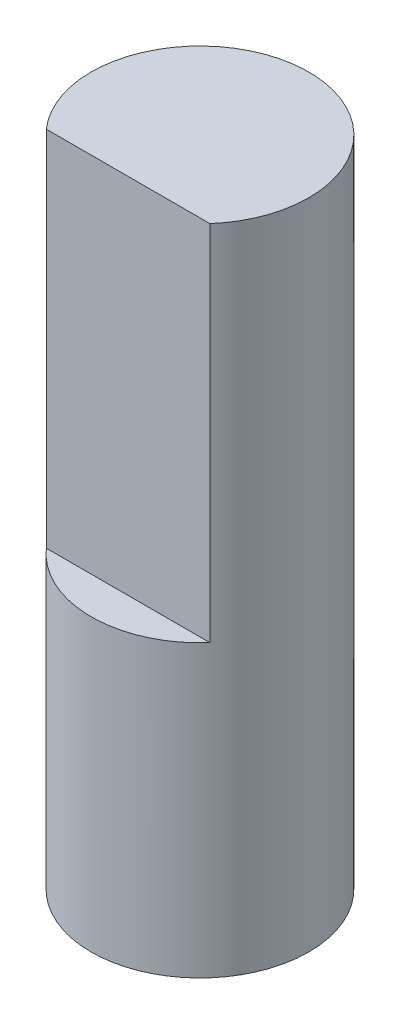
SolidWorks part; units mm, degrees
ref_plane "Front Plane" through (0, 0, 0) normal (0, 0, 1) x (1, 0, 0)
ref_plane "Top Plane" through (0, 0, 0) normal (0, 1, 0) x (1, 0, 0)
ref_plane "Right Plane" through (0, 0, 0) normal (1, 0, 0) x (0, 0, -1)
sketch "Sketch1" plane through (0, 0, 0) normal (0, 1, 0) x (1, 0, 0)
  circle A0 centre (0, 0) radius 1.5
  dimension "D1" = 3
extrude "Boss-Extrude1" add sketch "Sketch1" along normal blind 9
sketch "Sketch2" plane through (0, 9, 0) normal (0, 1, 0) x (1, 0, 0)
  line L0 (-1.1264, -0.9905) -> (1.1264, -0.9905)
  circle A0 centre (0, 0) radius 1.5 construction
  arc A1 (-1.1264, -0.9905) -> (1.1264, -0.9905) centre (0, 0) ccw
extrude "Cut-Extrude1" cut sketch "Sketch2" against normal blind 5
